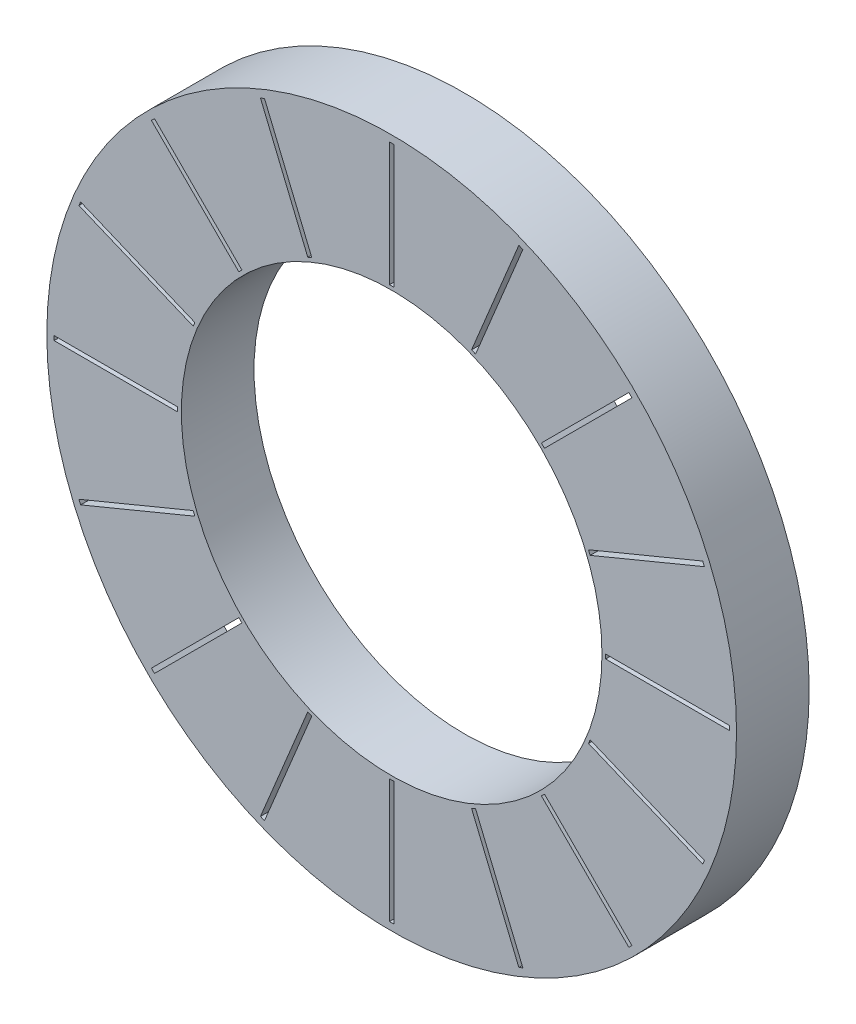
SolidWorks part; units mm, degrees
ref_plane "Plan de face" through (0, 0, 0) normal (0, 0, 1) x (1, 0, 0)
ref_plane "Plan de dessus" through (0, 0, 0) normal (0, 1, 0) x (1, 0, 0)
ref_plane "Plan de droite" through (0, 0, 0) normal (1, 0, 0) x (0, 0, -1)
sketch "Esquisse1" plane through (0, 0, 0) normal (0, 0, 1) x (1, 0, 0)
  circle A0 centre (0, 0) radius 46.4611
  dimension "D1" = 92.9222
extrude "Boss.-Extru.1" add sketch "Esquisse1" along normal blind 10
sketch "Esquisse2" plane through (0, 0, 10) normal (0, 0, 1) x (1, 0, 0)
  circle A0 centre (0, 0) radius 29.4448
  dimension "D1" = 58.8896
extrude "Enlèv. mat.-Extru.1" cut sketch "Esquisse2" against normal through all
sketch "Esquisse4" plane through (0, 0, 10) normal (0, 0, 1) x (1, 0, 0)
  line L0 (0, 46.4611) -> (0, -46.4611) construction
  line L1 (23.2382, 55.318) -> (7.9308, 18.3628)
  line L2 (-0.3, 60) -> (0.3, 60)
  line L3 (-0.3, 60) -> (-0.3, 20)
  line L4 (-0.3, 20) -> (0.3, 20)
  line L5 (0.3, 60) -> (0.3, 20)
  line L6 (22.6838, 55.5476) -> (7.3765, 18.5924)
  line L7 (22.6838, 55.5476) -> (23.2382, 55.318)
  line L8 (7.3765, 18.5924) -> (7.9308, 18.3628)
  line L9 (42.6385, 42.2143) -> (14.3543, 13.93)
  line L10 (42.2143, 42.6385) -> (13.93, 14.3543)
  line L11 (42.2143, 42.6385) -> (42.6385, 42.2143)
  line L12 (13.93, 14.3543) -> (14.3543, 13.93)
  line L13 (55.5476, 22.6838) -> (18.5924, 7.3765)
  line L14 (55.318, 23.2382) -> (18.3628, 7.9308)
  line L15 (55.318, 23.2382) -> (55.5476, 22.6838)
  line L16 (18.3628, 7.9308) -> (18.5924, 7.3765)
  line L17 (60, -0.3) -> (20, -0.3)
  line L18 (60, 0.3) -> (20, 0.3)
  line L19 (60, 0.3) -> (60, -0.3)
  line L20 (20, 0.3) -> (20, -0.3)
  line L21 (55.318, -23.2382) -> (18.3628, -7.9308)
  line L22 (55.5476, -22.6838) -> (18.5924, -7.3765)
  line L23 (55.5476, -22.6838) -> (55.318, -23.2382)
  line L24 (18.5924, -7.3765) -> (18.3628, -7.9308)
  line L25 (42.2143, -42.6385) -> (13.93, -14.3543)
  line L26 (42.6385, -42.2143) -> (14.3543, -13.93)
  line L27 (42.6385, -42.2143) -> (42.2143, -42.6385)
  line L28 (14.3543, -13.93) -> (13.93, -14.3543)
  line L29 (22.6838, -55.5476) -> (7.3765, -18.5924)
  line L30 (23.2382, -55.318) -> (7.9308, -18.3628)
  line L31 (23.2382, -55.318) -> (22.6838, -55.5476)
  line L32 (7.9308, -18.3628) -> (7.3765, -18.5924)
  line L33 (-0.3, -60) -> (-0.3, -20)
  line L34 (0.3, -60) -> (0.3, -20)
  line L35 (0.3, -60) -> (-0.3, -60)
  line L36 (0.3, -20) -> (-0.3, -20)
  line L37 (-23.2382, -55.318) -> (-7.9308, -18.3628)
  line L38 (-22.6838, -55.5476) -> (-7.3765, -18.5924)
  line L39 (-22.6838, -55.5476) -> (-23.2382, -55.318)
  line L40 (-7.3765, -18.5924) -> (-7.9308, -18.3628)
  line L41 (-42.6385, -42.2143) -> (-14.3543, -13.93)
  line L42 (-42.2143, -42.6385) -> (-13.93, -14.3543)
  line L43 (-42.2143, -42.6385) -> (-42.6385, -42.2143)
  line L44 (-13.93, -14.3543) -> (-14.3543, -13.93)
  line L45 (-55.5476, -22.6838) -> (-18.5924, -7.3765)
  line L46 (-55.318, -23.2382) -> (-18.3628, -7.9308)
  line L47 (-55.318, -23.2382) -> (-55.5476, -22.6838)
  line L48 (-18.3628, -7.9308) -> (-18.5924, -7.3765)
  line L49 (-60, 0.3) -> (-20, 0.3)
  line L50 (-60, -0.3) -> (-20, -0.3)
  line L51 (-60, -0.3) -> (-60, 0.3)
  line L52 (-20, -0.3) -> (-20, 0.3)
  line L53 (-55.318, 23.2382) -> (-18.3628, 7.9308)
  line L54 (-55.5476, 22.6838) -> (-18.5924, 7.3765)
  line L55 (-55.5476, 22.6838) -> (-55.318, 23.2382)
  line L56 (-18.5924, 7.3765) -> (-18.3628, 7.9308)
  line L57 (-42.2143, 42.6385) -> (-13.93, 14.3543)
  line L58 (-42.6385, 42.2143) -> (-14.3543, 13.93)
  line L59 (-42.6385, 42.2143) -> (-42.2143, 42.6385)
  line L60 (-14.3543, 13.93) -> (-13.93, 14.3543)
  line L61 (-22.6838, 55.5476) -> (-7.3765, 18.5924)
  line L62 (-23.2382, 55.318) -> (-7.9308, 18.3628)
  line L63 (-23.2382, 55.318) -> (-22.6838, 55.5476)
  line L64 (-7.9308, 18.3628) -> (-7.3765, 18.5924)
  circle A0 centre (0, 0) radius 46.4611 construction
  point P72 (0, 0)
  dimension "D1" = 0.6
  dimension "D2" = 20
  dimension "D3" = 40
  dimension "D4" = 16
extrude "Enlèv. mat.-Extru.2" cut sketch "Esquisse4" against normal blind 10
sketch "Esquisse5" plane through (0, 0, 0) normal (0, 0, 1) x (1, 0, 0)
  circle A0 centre (0, 0) radius 29.4448
extrude "Boss.-Extru.2" add sketch "Esquisse5" along normal blind 10
sketch "Esquisse6" plane through (0, 0, 10) normal (0, 0, 1) x (1, 0, 0)
  circle A0 centre (0, 0) radius 28.9448
  dimension "D1" = 57.8896
extrude "Enlèv. mat.-Extru.3" cut sketch "Esquisse6" against normal through all
sketch "Esquisse7" plane through (0, 0, 0) normal (0, 0, 1) x (1, 0, 0)
  circle A0 centre (0, 0) radius 46.4611
  circle A1 centre (0, 0) radius 47.4611
  dimension "D1" = 1
extrude "Boss.-Extru.3" add sketch "Esquisse7" along normal blind 10
